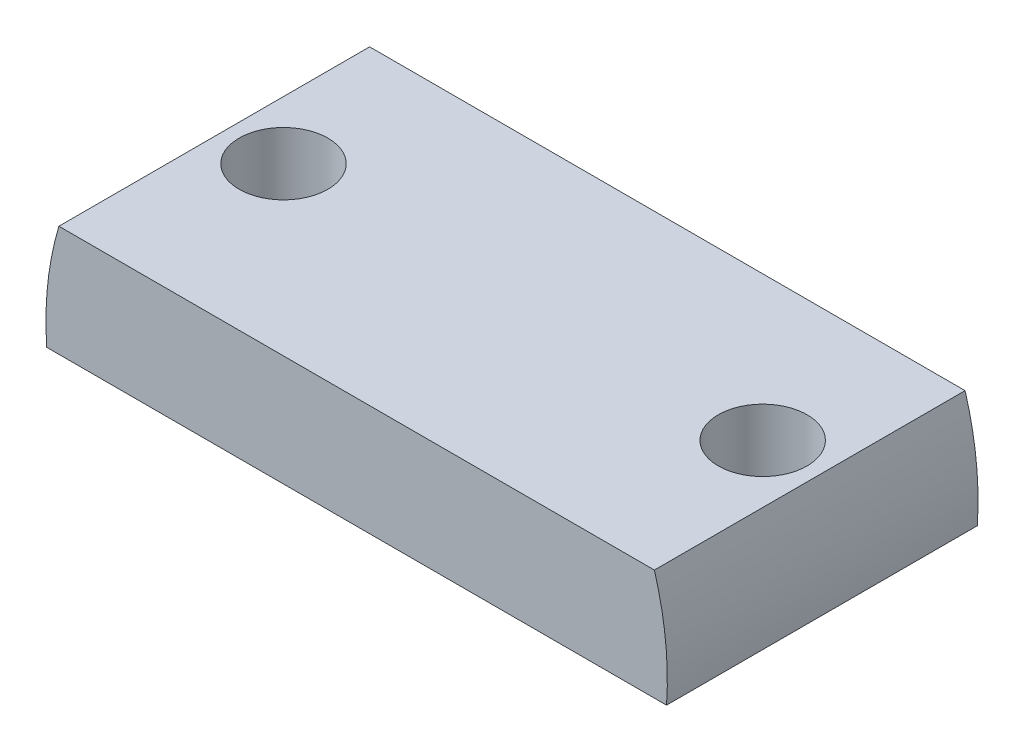
SolidWorks part; units mm, degrees
ref_plane "Front Plane" through (0, 0, 0) normal (0, 0, 1) x (1, 0, 0)
ref_plane "Top Plane" through (0, 0, 0) normal (0, 1, 0) x (1, 0, 0)
ref_plane "Right Plane" through (0, 0, 0) normal (1, 0, 0) x (0, 0, -1)
sketch "Sketch2" plane through (0, 0, 0) normal (0, 0, 1) x (1, 0, 0)
  line L0 (0, 0) -> (-13.9985, 0) construction
  line L1 (0, 0) -> (13.9985, 0) construction
  line L2 (0, 0) -> (0, 3.9996) construction
  line L3 (0, 3.9996) -> (-13.415, 3.9996)
  line L4 (0, 3.9996) -> (13.415, 3.9996)
  line L7 (0, 0) -> (0, -1) construction
  line L8 (0, -1) -> (-13.9627, -1)
  line L9 (0, -1) -> (13.9627, -1)
  arc A0 (-13.415, 3.9996) -> (-13.9627, -1) centre (0, 0) ccw
  arc A1 (13.9627, -1) -> (13.415, 3.9996) centre (0, 0) ccw
extrude "Boss-Extrude1" add sketch "Sketch2" along normal blind 15
ref_plane "Plane1" through (0, 3.9996, 0) normal (0, 1, 0) x (1, 0, 0)
sketch "Sketch3" plane through (0, 3.9996, 0) normal (0, 1, 0) x (1, 0, 0)
  line L0 (0, 0) -> (0, -15) construction
  line L1 (13.415, -15) -> (-13.415, -15) construction
  line L2 (10.795, -7.5) -> (0, -7.5) construction
  circle A0 centre (10.795, -7.5) radius 2
  circle A1 centre (-10.795, -7.5) radius 2
extrude "Cut-Extrude1" cut sketch "Sketch3" against normal through all
sketch "Sketch4" plane through (0, 0, 0) normal (0, 0, 1) x (1, 0, 0)
  line L0 (0, 0) -> (0, 3.9996) construction
  line L1 (8.25, 3.9996) -> (-8.25, 3.9996) construction
  line L2 (0, 3.9996) -> (0, -1) construction
  line L3 (-13.9627, -1) -> (13.9627, -1) construction
  line L4 (13.9627, -1) -> (-13.9627, -1)
  line L5 (0, 3.9996) -> (13.415, 3.9996)
  line L6 (0, 3.9996) -> (-13.415, 3.9996)
  arc A0 (-13.415, 3.9996) -> (-13.9627, -1) centre (0, 0) ccw
  arc A1 (13.9627, -1) -> (13.415, 3.9996) centre (0, 0) ccw
extrude "Cut-Extrude3" cut sketch "Sketch4" along normal blind 1
